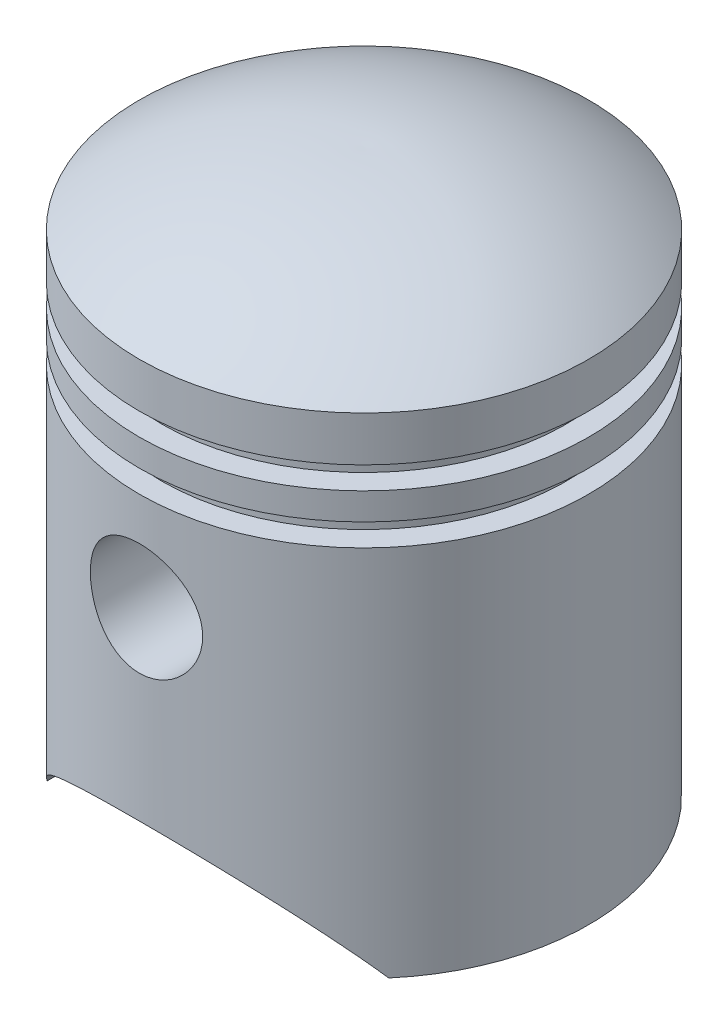
SolidWorks part; units mm, degrees
ref_plane "Front Plane" through (0, 0, 0) normal (0, 0, 1) x (1, 0, 0)
ref_plane "Top Plane" through (0, 0, 0) normal (0, 1, 0) x (1, 0, 0)
ref_plane "Right Plane" through (0, 0, 0) normal (1, 0, 0) x (0, 0, -1)
sketch "Sketch1" plane through (0, 0, 0) normal (0, 0, 1) x (1, 0, 0)
  line L0 (25, 0) -> (25, 41.5)
  line L1 (0, 62.5) -> (0, 0) construction
  line L2 (25, 49.5) -> (22.5, 49.5)
  line L3 (22.5, 49.5) -> (22.5, 47)
  line L4 (22.5, 47) -> (25, 47)
  line L5 (25, 44) -> (22.5, 44)
  line L6 (22.5, 44) -> (22.5, 41.5)
  line L7 (22.5, 41.5) -> (25, 41.5)
  line L8 (25, 49.5) -> (25, 54.5)
  line L9 (25, 44) -> (25, 47)
  line L10 (23, 0) -> (23, 39.5)
  line L11 (20.5, 39.5) -> (23, 39.5)
  line L12 (20.5, 45.5) -> (20.5, 39.5)
  line L13 (20.5, 45.5) -> (20.5, 45.5)
  line L14 (20.5, 45.5) -> (20.5, 45.5)
  line L15 (20.5, 45.5) -> (20.5, 45.5)
  line L16 (20.5, 51.5) -> (20.5, 45.5)
  line L17 (23, 51.5) -> (20.5, 51.5)
  line L18 (23, 51.5) -> (23, 53.4845)
  line L19 (25, 0) -> (23, 0)
  line L20 (0, 62.5) -> (0, 60.4994)
  arc A0 (25, 54.5) -> (0, 62.5) centre (0.9839, 22.5121) ccw
  arc A1 (23, 53.4845) -> (0, 60.4994) centre (0.9839, 22.5121) ccw
  arc A2 (23, 53.4845) -> (0.0492, 60.5006) centre (0.9839, 22.5121) ccw construction
  dimension "D1" = 25
  dimension "D4" = 40
  dimension "D2" = 54.5
  dimension "D3" = 62.5
  dimension "D5" = 5
  dimension "D6" = 3
  dimension "D7" = 2
revolve "Revolve1" add sketch "Sketch1" angle 360 about L1
sketch "Sketch3" plane through (0, 0, 0) normal (0, 0, 1) x (1, 0, 0)
  line L0 (-25, 0) -> (25, 0) construction
  line L1 (-19, 0) -> (19, 0)
  circle A0 centre (0, 30.5) radius 6.25
  arc A1 (19, 0) -> (-19, 0) centre (0, -13.05) ccw
  point P5 (0, 10)
  dimension "D1" = 32
  dimension "D2" = 10
  dimension "38" = 38
extrude "Cut-Extrude1" cut sketch "Sketch3" against normal through all both and the other way through all
sketch "Sketch4" plane through (0, 0, 0) normal (0, 0, 1) x (1, 0, 0)
  circle A0 centre (0, 30.5) radius 7.25
  circle A1 centre (0, 30.5) radius 6.25
extrude "Boss-Extrude1" add sketch "Sketch4" along normal up to surface (11.9257 mm away) from offset 12
mirror "Mirror1" about plane through (0, 0, 0) normal (0, 0, 1) of "Boss-Extrude1"
